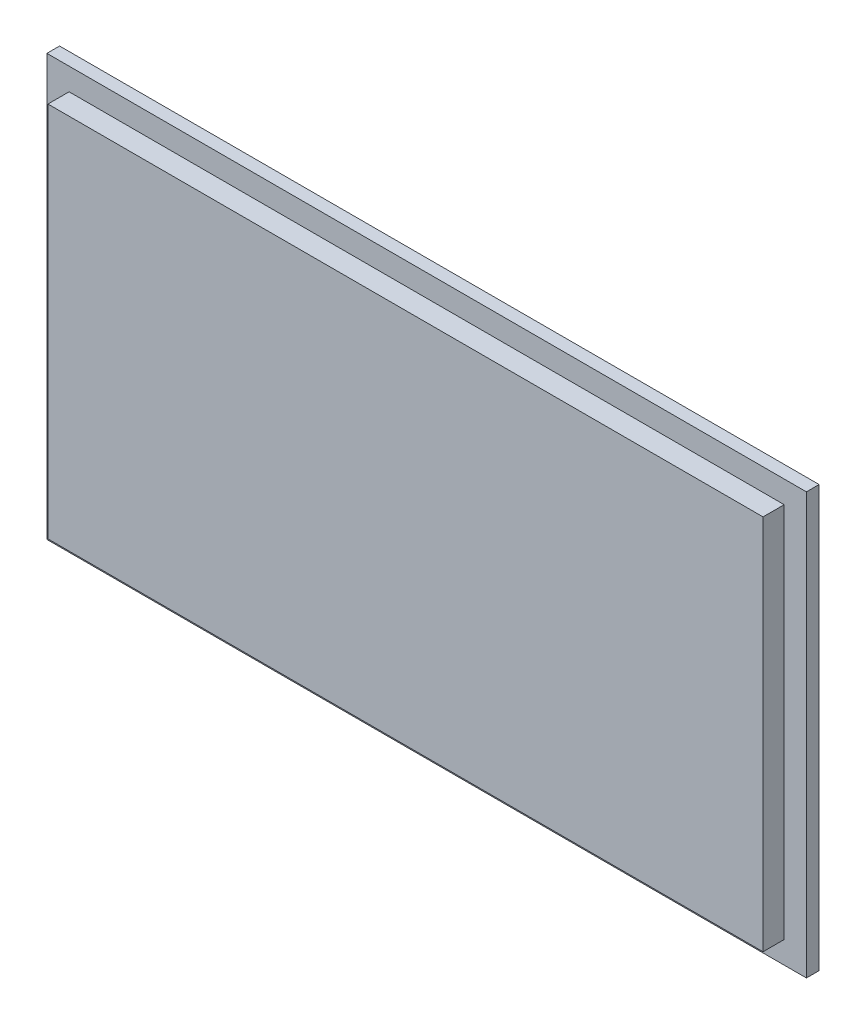
SolidWorks part; units mm, degrees
ref_plane "Přední rovina" through (0, 0, 0) normal (0, 0, 1) x (1, 0, 0)
ref_plane "Horní rovina" through (0, 0, 0) normal (0, 1, 0) x (1, 0, 0)
ref_plane "Pravá rovina" through (0, 0, 0) normal (1, 0, 0) x (0, 0, -1)
sketch "Skica1" plane through (0, 0, 0) normal (0, 0, 1) x (1, 0, 0)
  line L1 (0, 0) -> (179.5, 0)
  line L2 (0, 0) -> (0, 99.5)
  line L3 (0, 99.5) -> (179.5, 99.5)
  line L4 (179.5, 0) -> (179.5, 99.5)
  dimension "D1" = 99.5
  dimension "D2" = 179.5
extrude "Přidat vysunutím2" add sketch "Skica1" along normal blind 3 contours L2 L1 L4 L3
sketch "Skica2" plane through (0, 0, 3) normal (0, 0, 1) x (1, 0, 0)
  line L0 (0, 99.5) -> (179.5, 99.5) construction
  line L1 (5.25, 94.25) -> (174.25, 94.25)
  line L2 (5.25, 94.25) -> (5.25, 5.25)
  line L3 (5.25, 5.25) -> (174.25, 5.25)
  line L4 (174.25, 94.25) -> (174.25, 5.25)
  line L5 (0, 0) -> (0, 99.5) construction
  line L6 (0, 0) -> (179.5, 0) construction
  line L7 (179.5, 0) -> (179.5, 99.5) construction
  dimension "D1" = 5.25
  dimension "D2" = 5.25
  dimension "D3" = 5.25
  dimension "D4" = 5.25
extrude "Přidat vysunutím3" add sketch "Skica2" along normal blind 5
